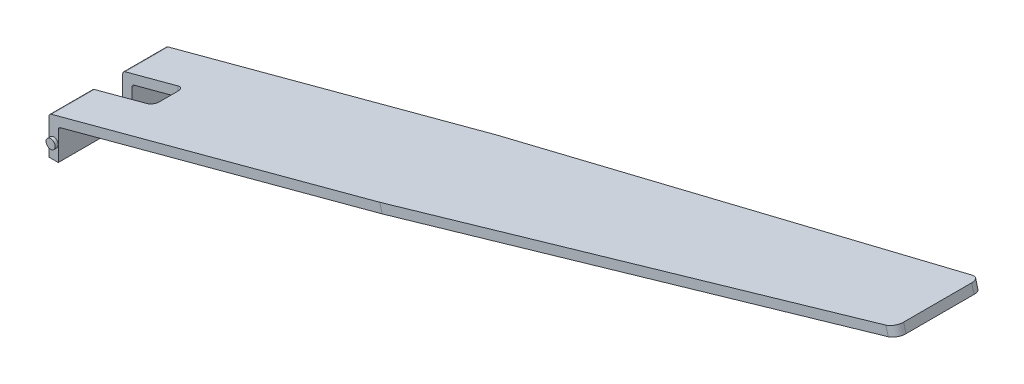
SolidWorks part; units mm, degrees
ref_plane "Front Plane" through (0, 0, 0) normal (0, 0, 1) x (1, 0, 0)
ref_plane "Top Plane" through (0, 0, 0) normal (0, 1, 0) x (1, 0, 0)
ref_plane "Right Plane" through (0, 0, 0) normal (1, 0, 0) x (0, 0, -1)
sketch "Profile Sketch" plane through (0, 0, 0) normal (0, 0, 1) x (1, 0, 0)
  line L0 (0, 0) -> (0, 1.2302)
  line L1 (0, 1.2302) -> (27.0459, 8.4771)
  line L2 (27.0459, 8.4771) -> (27.1236, 8.1874)
  line L3 (27.1236, 8.1874) -> (0.3, 1)
  line L4 (0.3, 1) -> (0.3, 0)
  line L5 (0.3, 0) -> (0, 0)
  dimension "D1" = 0.3
  dimension "D2" = 0.3
  dimension "D3" = 1
  dimension "D4" = 105
  dimension "D5" = 28
extrude "Profile Extrude" add sketch "Profile Sketch" along normal blind 3.8
chamfer "Chamfer Top" distance 0.5 angle 88.3 2 edges at (27.0847, 8.3322, 3.8) (27.0847, 8.3322, 0)
sketch "Sketch3" plane through (0, 0, 3.8) normal (0, 0, 1) x (1, 0, 0)
  circle A0 centre (0.15, 0.5) radius 0.15
  dimension "D1" = 0.3
  dimension "D2" = 0.15
  dimension "D3" = 0.5
extrude "Pins Extrude" add sketch "Sketch3" along normal blind 0.1 and the other way blind 3.9
sketch "Slot Sketch" plane through (0, 0, 0) normal (0, -1, 0) x (1, 0, 0)
  line L0 (0, 3.8) -> (0, 0) construction
  line L1 (0, 2.4) -> (2, 2.4)
  line L2 (0, 2.4) -> (0, 1.4)
  line L3 (0, 1.4) -> (2, 1.4)
  line L4 (2, 2.4) -> (2, 1.4)
  line L5 (0, 0) -> (0.3, 0) construction
  point P6 (2, 1.9)
  dimension "D1" = 2
  dimension "D2" = 1
  dimension "D3" = 1.9
extrude "Slot Cut" cut sketch "Slot Sketch" against normal blind 10
fillet "Fillet1" radius 0.1 4 edges at (0, 1.2302, 0.7) (0, 1.2302, 3.1) (0.3, 1, 0.7) (0.3, 1, 3.1)
fillet "Fillet2" radius 0.3 2 edges at (27.0847, 8.3322, 0.5) (27.0847, 8.3322, 3.3)
fillet "Fillet3" radius 0.2 2 edges at (2, 1.6108, 2.4) (2, 1.6108, 1.4)
